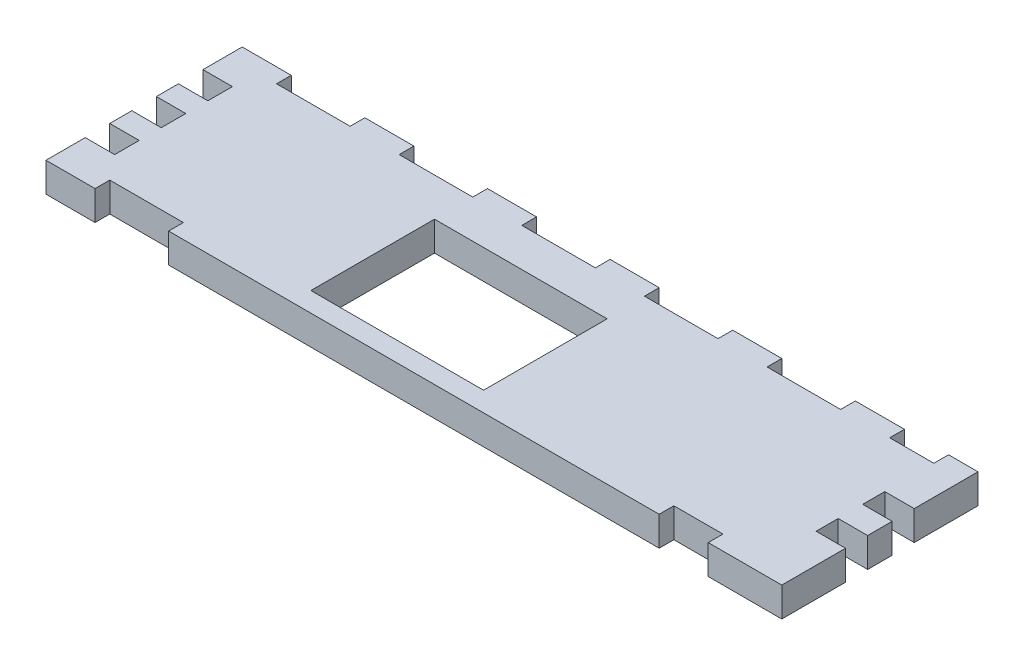
SolidWorks part; units mm, degrees
ref_plane "Спереди" through (0, 0, 0) normal (0, 0, 1) x (1, 0, 0)
ref_plane "Сверху" through (0, 0, 0) normal (0, 1, 0) x (1, 0, 0)
ref_plane "Справа" through (0, 0, 0) normal (1, 0, 0) x (0, 0, -1)
sketch "Эскиз1" plane through (0, 0, 0) normal (0, 1, 0) x (1, 0, 0)
  line L1 (0, 0) -> (150, 0)
  line L2 (0, 0) -> (0, -36)
  line L3 (0, -36) -> (150, -36)
  line L4 (150, 0) -> (150, -36)
  dimension "D1" = 36
  dimension "D2" = 150
extrude "Бобышка-Вытянуть2" add sketch "Эскиз1" along normal blind 6
sketch "Эскиз6" plane through (0, 0, 0) normal (0, 0, -1) x (-1, 0, 0)
  line L0 (22, 0) -> (-22, 0) construction
  line L1 (0, 6) -> (-10, 6)
  line L2 (0, 6) -> (0, 0)
  line L3 (0, 0) -> (-10, 0)
  line L4 (-10, 6) -> (-10, 0)
  dimension "D1" = 10
extrude "Бобышка-Вытянуть4" add sketch "Эскиз6" along normal blind 4
pattern_linear "Линейный массив1" count 6 spacing 25 along (1, 0, 0) of "Бобышка-Вытянуть4"
sketch "Эскиз8" plane through (0, 0, 0) normal (-1, 0, 0) x (0, 0, 1)
  line L0 (-4, 6) -> (36, 6) construction
  line L1 (4, 6) -> (9, 6)
  line L2 (4, 6) -> (4, 0)
  line L3 (4, 0) -> (9, 0)
  line L4 (9, 6) -> (9, 0)
  line L5 (-4, 0) -> (36, 0) construction
  line L6 (-4, 0) -> (-4, 6) construction
  line L7 (13.5, 6) -> (18.5, 6)
  line L8 (13.5, 6) -> (13.5, 0)
  line L9 (13.5, 0) -> (18.5, 0)
  line L10 (18.5, 6) -> (18.5, 0)
  line L11 (23.0048, 6) -> (28, 6)
  line L12 (23.0048, 6) -> (23.0048, 0)
  line L13 (23.0048, 0) -> (28, 0)
  line L14 (28, 6) -> (28, 0)
  line L15 (36, 6) -> (36, 0) construction
  dimension "D1" = 5
  dimension "D2" = 5
  dimension "D3" = 4.9952
  dimension "D4" = 8
  dimension "D5" = 8
  dimension "D6" = 4.5
extrude "Вырез-Вытянуть3" cut sketch "Эскиз8" against normal blind 6
sketch "Эскиз9" plane through (0, 6, 0) normal (0, 1, 0) x (1, 0, 0)
  line L0 (6, -4) -> (150, -4) construction
  line L1 (150, -36) -> (150, 0) construction
  line L2 (6, -9) -> (150, -9) construction
  line L3 (6, -13.5) -> (150, -13.5) construction
  line L4 (6, -18.5) -> (150, -18.5) construction
  line L5 (6, -23.0048) -> (150, -23.0048) construction
  line L6 (6, -28) -> (150, -28) construction
sketch "Эскиз11" plane through (150, 0, 0) normal (1, 0, 0) x (0, 0, -1)
  line L0 (-23.0048, 6) -> (-23.0048, 0) construction
  line L5 (22, 0) -> (-22, 0) construction
  line L6 (-18.5, 6) -> (-18.5, 0) construction
  line L7 (-36, 0) -> (0, 0) construction
  line L8 (-13.5, 6) -> (-13.5, 0) construction
  line L9 (-9, 6) -> (-9, 0) construction
  line L11 (-23.0048, 6) -> (-18.5, 6)
  line L12 (-23.0048, 6) -> (-23.0048, 0)
  line L13 (-23.0048, 0) -> (-18.5, 0)
  line L14 (-18.5, 6) -> (-18.5, 0)
  line L15 (-13.5, 6) -> (-9, 6)
  line L16 (-13.5, 6) -> (-13.5, 0)
  line L17 (-13.5, 0) -> (-9, 0)
  line L18 (-9, 6) -> (-9, 0)
extrude "Вырез-Вытянуть4" cut sketch "Эскиз11" against normal blind 6
sketch "Эскиз12" plane through (0, 6, 0) normal (0, 1, 0) x (1, 0, 0)
  line L0 (0, -18.5) -> (0, -23.0048) construction
  line L1 (50, -6.8) -> (85.2, -6.8)
  line L2 (50, -6.8) -> (50, -32)
  line L3 (50, -32) -> (85.2, -32)
  line L4 (85.2, -6.8) -> (85.2, -32)
  line L5 (0, -36) -> (150, -36) construction
  dimension "D1" = 35.2
  dimension "D2" = 25.2
  dimension "D3" = 50
  dimension "D4" = 4
extrude "Вырез-Вытянуть5" cut sketch "Эскиз12" against normal through all
sketch "Эскиз13" plane through (0, 6, 0) normal (0, 1, 0) x (1, 0, 0)
  line L0 (10, 0) -> (10, -36) construction
  line L1 (0, -36) -> (150, -36) construction
  line L2 (25, 0) -> (25, -36) construction
  line L3 (125, 0) -> (125, -36) construction
  line L4 (135, 0) -> (135, -36) construction
sketch "Эскиз14" plane through (0, 0, 36) normal (0, 0, 1) x (1, 0, 0)
  line L0 (0, 0) -> (150, 0) construction
  line L1 (10, 6) -> (25, 6)
  line L2 (10, 6) -> (10, 0)
  line L3 (10, 0) -> (25, 0)
  line L4 (25, 6) -> (25, 0)
  line L6 (125, 6) -> (135, 6)
  line L7 (125, 6) -> (125, 0)
  line L8 (125, 0) -> (135, 0)
  line L9 (135, 6) -> (135, 0)
  dimension "D1" = 15
  dimension "D2" = 10
extrude "Вырез-Вытянуть6" cut sketch "Эскиз14" against normal blind 4
sketch "Эскиз15" plane through (0, 0, 0) normal (0, 0, -1) x (-1, 0, 0)
  line L1 (-25, 6) -> (-10, 6)
  line L2 (-25, 6) -> (-25, 0)
  line L3 (-25, 0) -> (-10, 0)
  line L4 (-10, 6) -> (-10, 0)
extrude "Бобышка-Вытянуть5" add sketch "Эскиз15" along normal blind 1
pattern_linear "Линейный массив2" count 5 spacing 25 along (1, 0, 0) of "Бобышка-Вытянуть5"
sketch "Эскиз16" plane through (0, 0, 0) normal (0, 0, -1) x (-1, 0, 0)
  line L1 (-150, 6) -> (-135, 6)
  line L2 (-150, 6) -> (-150, 0)
  line L3 (-150, 0) -> (-135, 0)
  line L4 (-135, 6) -> (-135, 0)
extrude "Бобышка-Вытянуть6" add sketch "Эскиз16" along normal blind 1
sketch "Эскиз17" plane through (0, 0, 32) normal (0, 0, 1) x (1, 0, 0)
  line L0 (22, 0) -> (-22, 0) construction
  line L1 (125, 6) -> (135, 6)
  line L2 (125, 6) -> (125, 0)
  line L3 (125, 0) -> (135, 0)
  line L4 (135, 6) -> (135, 0)
  line L5 (135, 0) -> (135, 6) construction
extrude "Бобышка-Вытянуть7" add sketch "Эскиз17" along normal blind 1
sketch "Эскиз18" plane through (0, 0, 32) normal (0, 0, 1) x (1, 0, 0)
  line L0 (22, 0) -> (-22, 0) construction
  line L1 (10, 6) -> (25, 6)
  line L2 (10, 6) -> (10, 0)
  line L3 (10, 0) -> (25, 0)
  line L4 (25, 6) -> (25, 0)
  line L5 (25, 0) -> (25, 6) construction
extrude "Бобышка-Вытянуть8" add sketch "Эскиз18" along normal blind 1
sketch "Эскиз19" plane through (0, 0, -1) normal (0, 0, -1) x (-1, 0, 0)
  line L0 (22, 0) -> (-22, 0) construction
  line L1 (-150, 6) -> (-144, 6)
  line L2 (-150, 6) -> (-150, 0)
  line L3 (-150, 0) -> (-144, 0)
  line L4 (-144, 6) -> (-144, 0)
  dimension "D1" = 6
extrude "Бобышка-Вытянуть9" add sketch "Эскиз19" along normal blind 3
